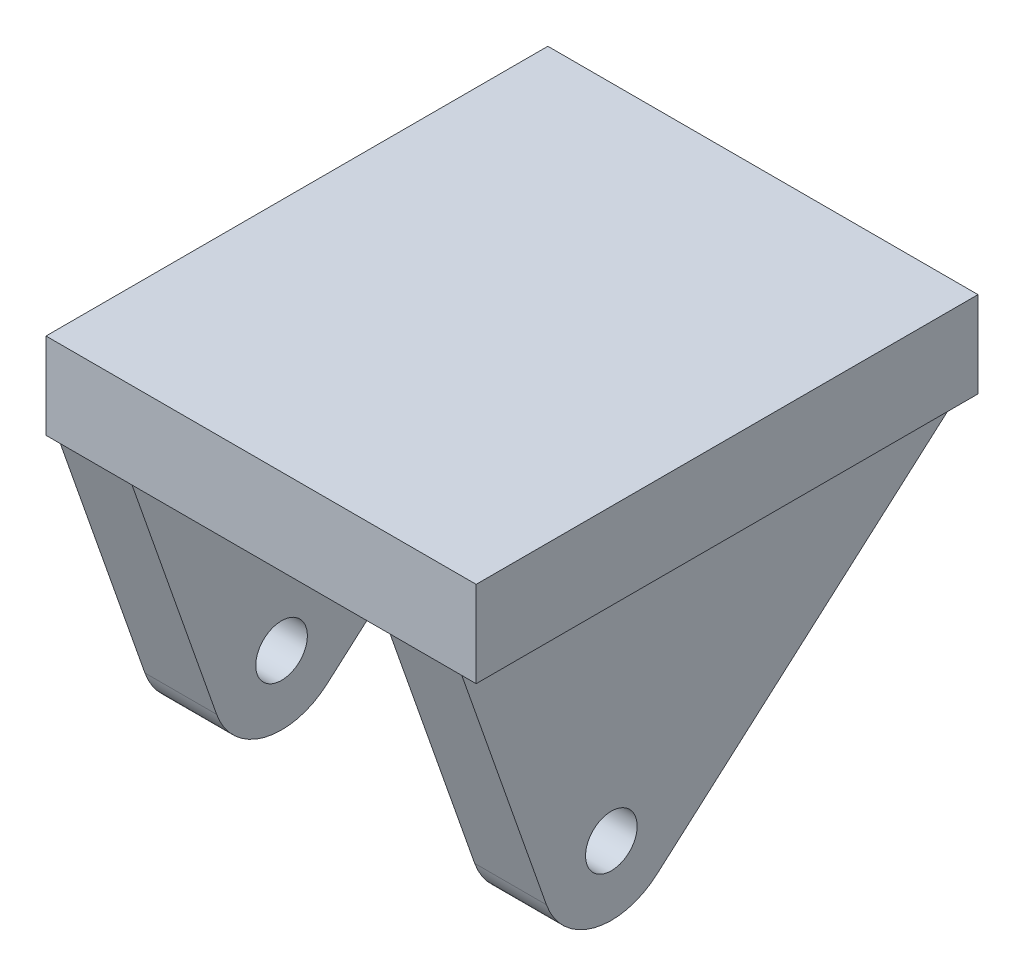
SolidWorks part; units mm, degrees
ref_plane "Plan de face" through (0, 0, 0) normal (0, 0, 1) x (1, 0, 0)
ref_plane "Plan de dessus" through (0, 0, 0) normal (0, 1, 0) x (1, 0, 0)
ref_plane "Plan de droite" through (0, 0, 0) normal (1, 0, 0) x (0, 0, -1)
sketch "Esquisse1" plane through (0, 0, 0) normal (0, 0, 1) x (1, 0, 0)
  line L1 (-15, 0) -> (15, 0)
  line L2 (-15, 0) -> (-15, -6)
  line L3 (-15, -6) -> (15, -6)
  line L4 (15, 0) -> (15, -6)
  dimension "D1" = 6
  dimension "D2" = 30
  dimension "D3" = 15
extrude "Boss.-Extru.1" add sketch "Esquisse1" along normal mid plane 35
sketch "Esquisse2" plane through (0, 0, 0) normal (0, 1, 0) x (1, 0, 0)
  line L0 (0, 0) -> (-11.7202, 0) construction
  line L1 (0, 0) -> (0, 12.5609) construction
  point P0 (0, 0)
ref_plane "Plan1" through (0, 0, 0) normal (0, 0.7071, 0.7071) x (1, 0, 0)
ref_plane "Plan2" through (0, 0, 0) normal (0, 0.7071, -0.7071) x (-1, 0, 0)
ref_plane "Plan3" through (14, 0, 0) normal (1, 0, 0) x (0, 0, -1)
sketch "Esquisse3" plane through (14, 0, 0) normal (1, 0, 0) x (0, 0, -1)
  line L0 (-17.5, -6) -> (17.5, -6) construction
  line L1 (-17.5, -6) -> (17.5, -6)
  line L2 (-17.5, -6) -> (-11.6, -22.8034)
  line L3 (17.5, -6) -> (-3.9015, -24.8179)
  circle A0 centre (-7.0711, -21.2132) radius 1.8 construction
  circle A1 centre (-7.0711, -21.2132) radius 1.8
  arc A2 (-11.6, -22.8034) -> (-3.9015, -24.8179) centre (-7.0711, -21.2132) ccw
  circle A4 centre (-7.0711, -21.2132) radius 4.8 construction
  point P7 (-2.2711, -21.2132)
  dimension "D1" = 3
extrude "Boss.-Extru.2" add sketch "Esquisse3" against normal blind 5
pattern_linear "Répétition linéaire1" count 2 spacing 23 along (-1, 0, 0) of "Boss.-Extru.2"
